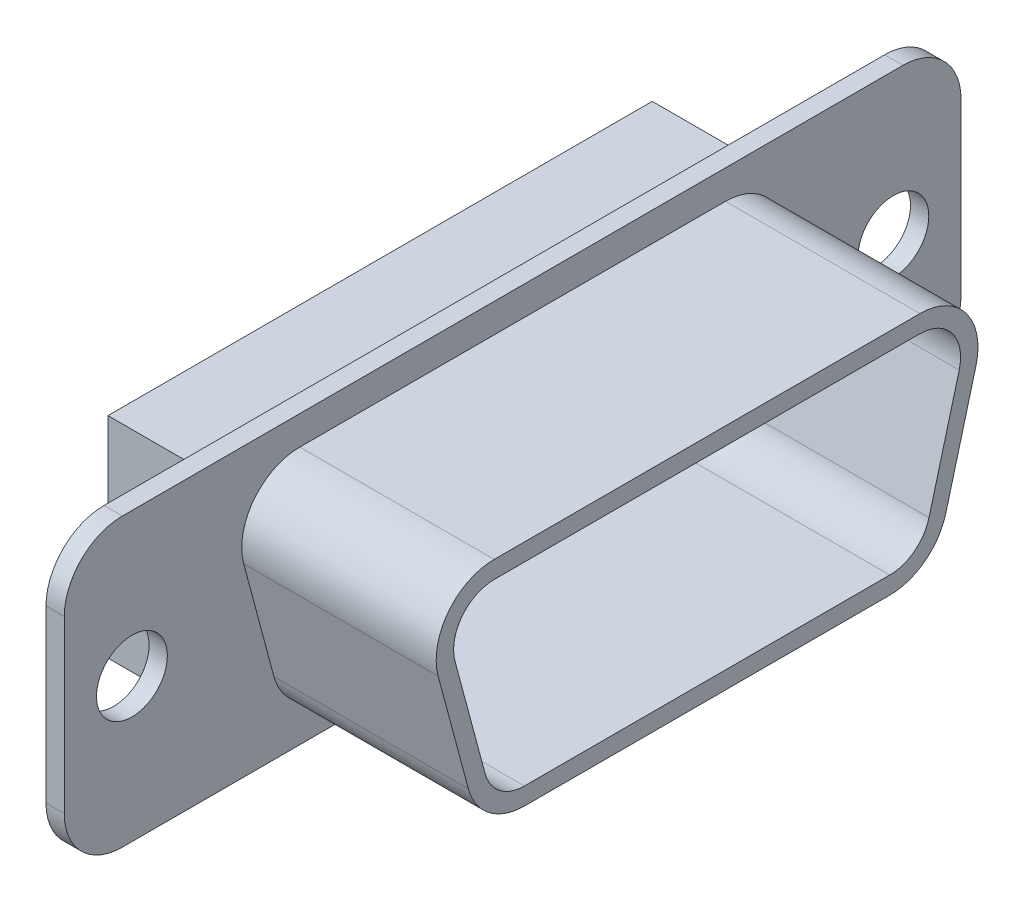
SolidWorks part; units mm, degrees
ref_plane "Front Plane" through (0, 0, 0) normal (0, 0, 1) x (1, 0, 0)
ref_plane "Top Plane" through (0, 0, 0) normal (0, 1, 0) x (1, 0, 0)
ref_plane "Right Plane" through (0, 0, 0) normal (1, 0, 0) x (0, 0, -1)
sketch "Sketch1" plane through (0, 0, 0) normal (1, 0, 0) x (0, 0, -1)
  line L1 (-17.08, -6.275) -> (17.08, -6.275)
  line L2 (-19.62, -3.735) -> (-19.62, 3.735)
  line L3 (-17.08, 6.275) -> (17.08, 6.275)
  line L4 (19.62, -3.735) -> (19.62, 3.735)
  line L5 (-19.62, -6.275) -> (19.62, 6.275) construction
  line L6 (-19.62, 6.275) -> (19.62, -6.275) construction
  arc A0 (19.62, 3.735) -> (17.08, 6.275) centre (17.08, 3.735) ccw
  arc A1 (17.08, -6.275) -> (19.62, -3.735) centre (17.08, -3.735) ccw
  arc A2 (-17.08, -6.275) -> (-19.62, -3.735) centre (-17.08, -3.735) cw
  arc A3 (-17.08, 6.275) -> (-19.62, 3.735) centre (-17.08, 3.735) ccw
  point P0 (0, 0)
  dimension "D3" = 2.54
  dimension "D1" = 39.24
  dimension "D2" = 12.55
extrude "Boss-Extrude1" add sketch "Sketch1" along normal blind 0.8
sketch "Sketch2" plane through (0.8, 0, 0) normal (1, 0, 0) x (0, 0, -1)
  line L0 (-9.3148, 5.005) -> (9.3148, 5.005)
  line L1 (-7.9938, -5.005) -> (7.9938, -5.005)
  line L2 (10.4473, -3.1224) -> (11.7683, 1.8076)
  line L3 (-10.4473, -3.1224) -> (-11.7683, 1.8076)
  line L6 (0, 0) -> (0, 7.874) construction
  line L7 (-12.625, 5.005) -> (-12.625, -6.275) construction
  line L8 (12.625, 5.005) -> (12.625, -6.275) construction
  line L9 (17.08, 6.275) -> (-17.08, 6.275) construction
  line L10 (-17.08, -6.275) -> (17.08, -6.275) construction
  arc A0 (-11.7683, 1.8076) -> (-9.3148, 5.005) centre (-9.3148, 2.465) cw
  arc A1 (9.3148, 5.005) -> (11.7683, 1.8076) centre (9.3148, 2.465) cw
  arc A2 (10.4473, -3.1224) -> (7.9938, -5.005) centre (7.9938, -2.465) cw
  arc A3 (-10.4473, -3.1224) -> (-7.9938, -5.005) centre (-7.9938, -2.465) ccw
  dimension "D6" = 2.54
  dimension "D1" = 1.27
  dimension "D2" = 1.27
  dimension "D3" = 25.25
  dimension "D4" = 15
  dimension "D5" = 15
extrude "Boss-Extrude2" add sketch "Sketch2" along normal blind 8.509
sketch "Sketch3" plane through (9.309, 0, 0) normal (1, 0, 0) x (0, 0, -1)
  line L8 (-11.0322, 2.0048) -> (-9.7112, -2.9252)
  line L9 (-7.9938, -4.243) -> (7.9938, -4.243)
  line L10 (9.7112, -2.9252) -> (11.0322, 2.0048)
  line L11 (9.3148, 4.243) -> (-9.3148, 4.243)
  line L12 (-11.0322, 2.0048) -> (-9.7112, -2.9252)
  line L13 (-7.9938, -4.243) -> (7.9938, -4.243)
  line L14 (9.7112, -2.9252) -> (11.0322, 2.0048)
  line L15 (9.3148, 4.243) -> (-9.3148, 4.243)
  arc A8 (-9.3148, 4.243) -> (-11.0322, 2.0048) centre (-9.3148, 2.465) ccw
  arc A9 (-9.7112, -2.9252) -> (-7.9938, -4.243) centre (-7.9938, -2.465) ccw
  arc A10 (7.9938, -4.243) -> (9.7112, -2.9252) centre (7.9938, -2.465) ccw
  arc A11 (11.0322, 2.0048) -> (9.3148, 4.243) centre (9.3148, 2.465) ccw
  arc A12 (-9.3148, 4.243) -> (-11.0322, 2.0048) centre (-9.3148, 2.465) ccw
  arc A13 (-9.7112, -2.9252) -> (-7.9938, -4.243) centre (-7.9938, -2.465) ccw
  arc A14 (7.9938, -4.243) -> (9.7112, -2.9252) centre (7.9938, -2.465) ccw
  arc A15 (11.0322, 2.0048) -> (9.3148, 4.243) centre (9.3148, 2.465) ccw
  dimension "D1" = 0.762
extrude "Cut-Extrude1" cut sketch "Sketch3" against normal blind 8.509
hole_wizard "X (0.397) Diameter Hole1" positions "Sketch5" profile "Sketch6" hole size "X" standard "ANSI Inch" end condition through all
sketch "Sketch5" plane through (0.8, 0, 0) normal (1, 0, 0) x (0, 0, -1)
  line L0 (0, 0) -> (0, 15.6354) construction
  point P0 (-16.66, 0)
  point P2 (16.66, 0)
  dimension "D1" = 33.32
sketch "Sketch6" plane through (0.8, 0, 16.66) normal (0, 1, 0) x (0, 0, -1)
  line L0 (0, 0) -> (0, 0.8)
  line L1 (0, 0.8) -> (1.55, 0.8)
  line L2 (1.55, 0.8) -> (1.55, 0)
  line L5 (1.55, 0) -> (0, 0)
  line L11 (0, -6.35) -> (0, 107.95) construction
  dimension "Thru Hole Dia." = 3.1
  dimension "Thru Hole Depth" = 0.8
sketch "Sketch8" plane through (0, 0, 0) normal (-1, 0, 0) x (0, 0, 1)
  line L1 (-11.909, -4.5958) -> (11.909, -4.5958)
  line L2 (-11.909, -4.5958) -> (-11.909, 4.5958)
  line L3 (-11.909, 4.5958) -> (11.909, 4.5958)
  line L4 (11.909, -4.5958) -> (11.909, 4.5958)
  line L5 (-11.909, -4.5958) -> (11.909, 4.5958) construction
  line L6 (-11.909, 4.5958) -> (11.909, -4.5958) construction
  point P0 (0, 0)
extrude "Boss-Extrude4" add sketch "Sketch8" along normal blind 5
